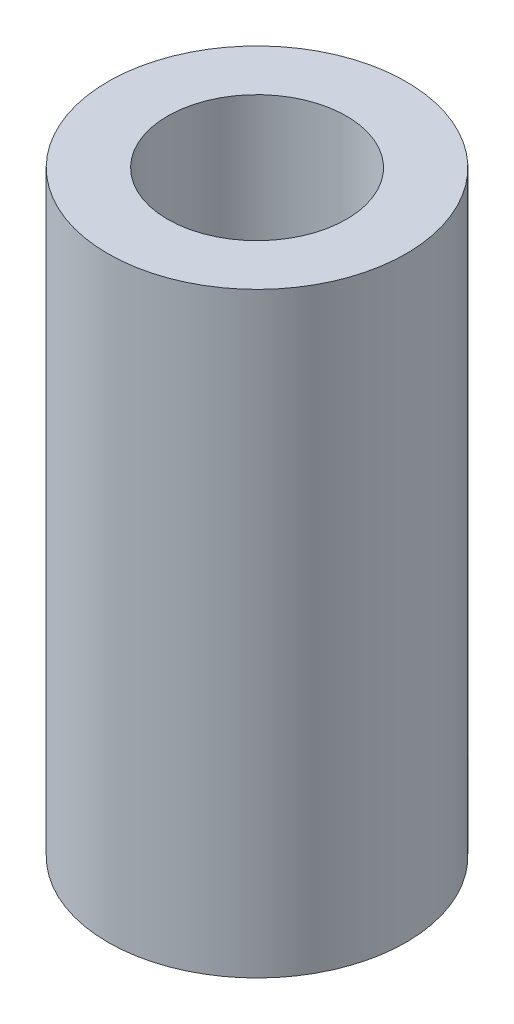
SolidWorks part; units mm, degrees
material "ABS"
ref_plane "Plan de face" through (0, 0, 0) normal (0, 0, 1) x (1, 0, 0)
ref_plane "Plan de dessus" through (0, 0, 0) normal (0, 1, 0) x (1, 0, 0)
ref_plane "Plan de droite" through (0, 0, 0) normal (1, 0, 0) x (0, 0, -1)
sketch "Esquisse1" plane through (0, 0, 0) normal (0, 1, 0) x (1, 0, 0)
  circle A0 centre (0, 0) radius 2.5
  circle A1 centre (0, 0) radius 1.5
  dimension "D1" = 5
  dimension "D2" = 3
extrude "Boss.-Extru.1" add sketch "Esquisse1" along normal blind 10
